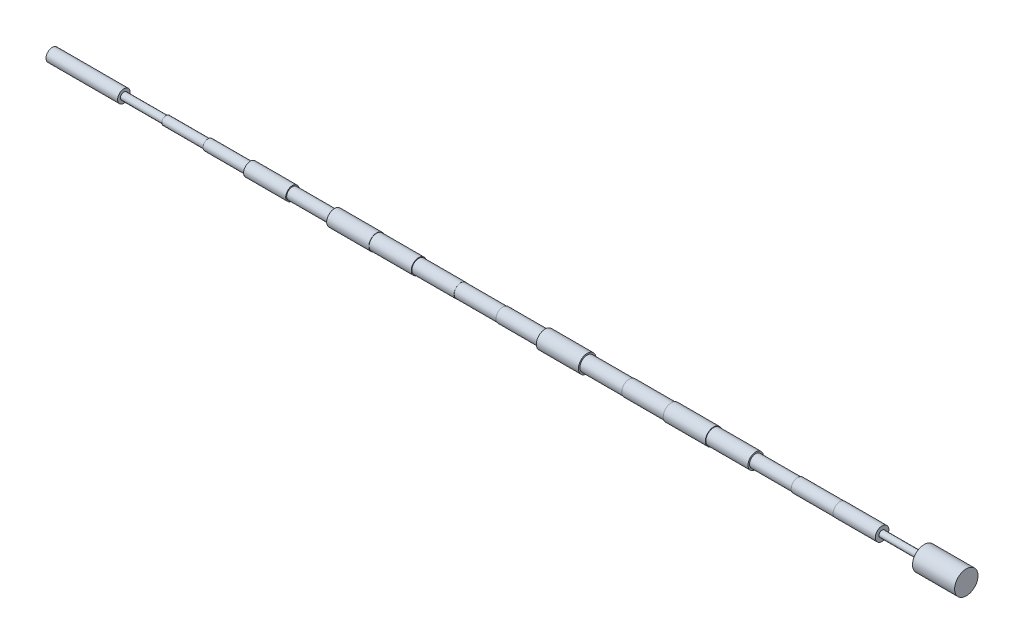
SolidWorks part; units mm, degrees
ref_plane "Front Plane" through (0, 0, 0) normal (0, 0, 1) x (1, 0, 0)
ref_plane "Top Plane" through (0, 0, 0) normal (0, 1, 0) x (1, 0, 0)
ref_plane "Right Plane" through (0, 0, 0) normal (1, 0, 0) x (0, 0, -1)
sketch "Sketch1" plane through (0, 0, 0) normal (0, 0, 1) x (1, 0, 0)
  line L1 (0, 0) -> (10, 0)
  line L2 (0, 0) -> (0, 0.831)
  line L3 (0, 0.831) -> (10, 0.831)
  line L4 (10, 0) -> (10, 0.831)
  line L5 (10, 0) -> (20, 0)
  line L6 (10, 0) -> (10, 1.008)
  line L7 (10, 1.008) -> (20, 1.008)
  line L8 (20, 0) -> (20, 1.008)
  line L9 (20, 0) -> (30, 0)
  line L10 (20, 0) -> (20, 1.222)
  line L11 (20, 1.222) -> (30, 1.222)
  line L12 (30, 0) -> (30, 1.222)
  line L13 (30, 0) -> (40, 0)
  line L14 (30, 0) -> (30, 1.59)
  line L15 (30, 1.59) -> (40, 1.59)
  line L16 (40, 0) -> (40, 1.59)
  line L17 (40, 0) -> (50, 0)
  line L18 (40, 0) -> (40, 1.354)
  line L19 (40, 1.354) -> (50, 1.354)
  line L20 (50, 0) -> (50, 1.354)
  line L21 (50, 0) -> (60, 0)
  line L22 (50, 0) -> (50, 1.867)
  line L23 (50, 1.867) -> (60, 1.867)
  line L24 (60, 0) -> (60, 1.867)
  line L25 (60, 0) -> (70, 0)
  line L26 (60, 0) -> (60, 1.783)
  line L27 (60, 1.783) -> (70, 1.783)
  line L28 (70, 0) -> (70, 1.783)
  line L29 (70, 0) -> (80, 0)
  line L30 (70, 0) -> (70, 1.623)
  line L31 (70, 1.623) -> (80, 1.623)
  line L32 (80, 0) -> (80, 1.623)
  line L33 (80, 0) -> (90, 0)
  line L34 (80, 0) -> (80, 1.581)
  line L35 (80, 1.581) -> (90, 1.581)
  line L36 (90, 0) -> (90, 1.581)
  line L37 (90, 0) -> (100, 0)
  line L38 (90, 0) -> (90, 1.655)
  line L39 (90, 1.655) -> (100, 1.655)
  line L40 (100, 0) -> (100, 1.655)
  line L41 (100, 0) -> (110, 0)
  line L42 (100, 0) -> (100, 2.092)
  line L43 (100, 2.092) -> (110, 2.092)
  line L44 (110, 0) -> (110, 2.092)
  line L45 (110, 0) -> (120, 0)
  line L46 (110, 0) -> (110, 1.737)
  line L47 (110, 1.737) -> (120, 1.737)
  line L48 (120, 0) -> (120, 1.737)
  line L49 (120, 0) -> (130, 0)
  line L50 (120, 0) -> (120, 1.808)
  line L51 (120, 1.808) -> (130, 1.808)
  line L52 (130, 0) -> (130, 1.808)
  line L53 (130, 0) -> (140, 0)
  line L54 (130, 0) -> (130, 1.957)
  line L55 (130, 1.957) -> (140, 1.957)
  line L56 (140, 0) -> (140, 1.957)
  line L57 (140, 0) -> (150, 0)
  line L58 (140, 0) -> (140, 1.826)
  line L59 (140, 1.826) -> (150, 1.826)
  line L60 (150, 0) -> (150, 1.826)
  line L61 (150, 0) -> (160, 0)
  line L62 (150, 0) -> (150, 1.458)
  line L63 (150, 1.458) -> (160, 1.458)
  line L64 (160, 0) -> (160, 1.458)
  line L65 (160, 0) -> (170, 0)
  line L66 (160, 0) -> (160, 1.573)
  line L67 (160, 1.573) -> (170, 1.573)
  line L68 (170, 0) -> (170, 1.573)
  line L69 (170, 0) -> (180, 0)
  line L70 (170, 0) -> (170, 1.608)
  line L71 (170, 1.608) -> (180, 1.608)
  line L72 (180, 0) -> (180, 1.608)
  line L73 (180, 0) -> (190, 0)
  line L74 (180, 0) -> (180, 0.738)
  line L75 (180, 0.738) -> (190, 0.738)
  line L76 (190, 0) -> (190, 0.738)
  line L77 (190, 0) -> (200, 0)
  line L78 (190, 0) -> (190, 2.782)
  line L79 (190, 2.782) -> (200, 2.782)
  line L80 (200, 0) -> (200, 2.782)
  dimension "R1" = 0.831
  dimension "R2" = 1.008
  dimension "R3" = 1.222
  dimension "R4" = 1.59
  dimension "R5" = 1.354
  dimension "R6" = 1.867
  dimension "R7" = 1.783
  dimension "R8" = 1.623
  dimension "R9" = 1.581
  dimension "R10" = 1.655
  dimension "R20" = 2.782
  dimension "R19" = 0.738
  dimension "R18" = 1.608
  dimension "R17" = 1.573
  dimension "R16" = 1.458
  dimension "R15" = 1.826
  dimension "R14" = 1.957
  dimension "R13" = 1.808
  dimension "R12" = 1.737
  dimension "R11" = 2.092
revolve "Revolve1" add sketch "Sketch1" angle 360 about L1
sketch "Sketch2" plane through (0, 0, 0) normal (-1, 0, 0) x (0, 0, 1)
  circle A0 centre (0, 0) radius 1.5
  dimension "D1" = 3
extrude "Boss-Extrude1" add sketch "Sketch2" along normal blind 17
equation "\"L\"=200"
equation "\"num_design_vars\"=20"
